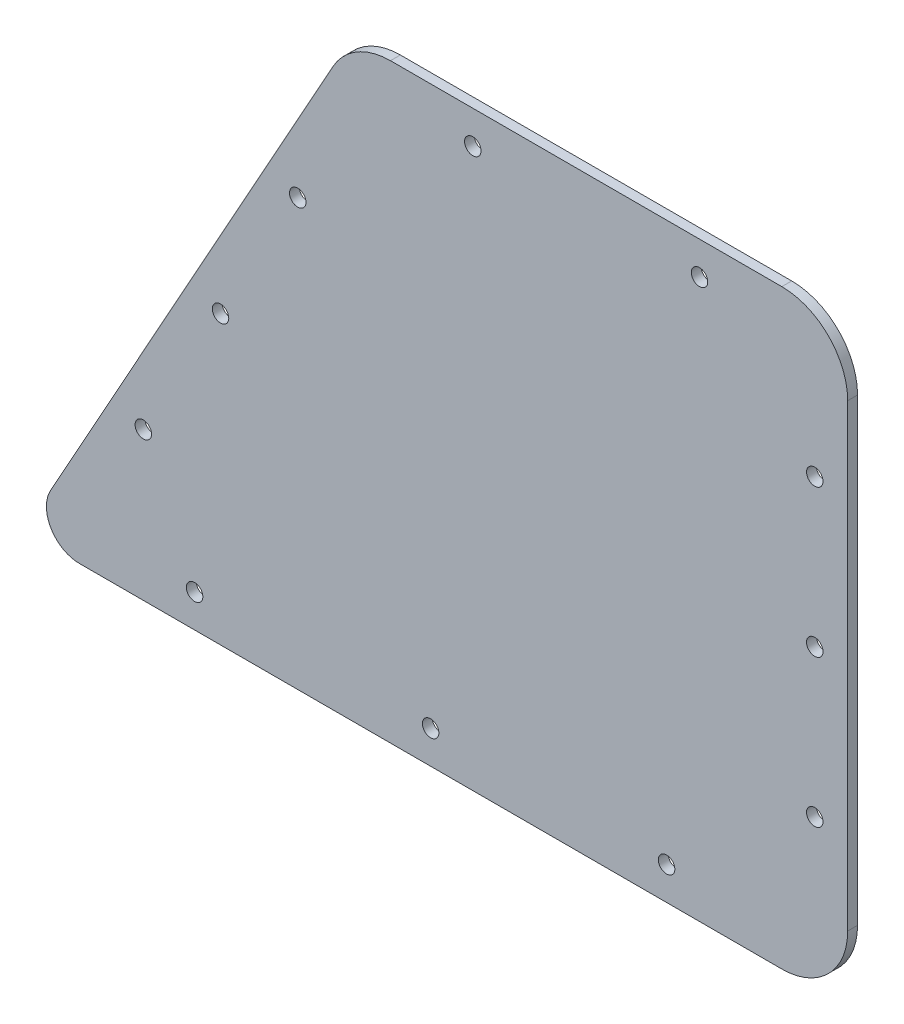
SolidWorks part; units mm, degrees
ref_plane "Front Plane" through (0, 0, 0) normal (0, 0, 1) x (1, 0, 0)
ref_plane "Top Plane" through (0, 0, 0) normal (0, 1, 0) x (1, 0, 0)
ref_plane "Right Plane" through (0, 0, 0) normal (1, 0, 0) x (0, 0, -1)
sketch "Sketch1" plane through (0, 0, 0) normal (0, 0, 1) x (1, 0, 0)
  line L0 (-1232.9818, 0) -> (48767.0182, 0) construction
  line L1 (-59.4361, 179.5) -> (59.4361, 179.5)
  line L2 (-76.9192, 169.2129) -> (-162.6728, 14.8564)
  line L3 (-153.9312, 0) -> (59.4361, 0)
  line L4 (79.4361, 20) -> (79.4361, 159.5)
  arc A0 (-153.9312, 0) -> (-162.6728, 14.8564) centre (-153.9312, 10) cw
  arc A1 (59.4361, 0) -> (79.4361, 20) centre (59.4361, 20) ccw
  arc A2 (79.4361, 159.5) -> (59.4361, 179.5) centre (59.4361, 159.5) ccw
  arc A3 (-76.9192, 169.2129) -> (-59.4361, 179.5) centre (-59.4361, 159.5) cw
  point P3 (0, 179.5)
  dimension "D1" = 10
  dimension "D2" = 20
  dimension "D3" = 20
  dimension "D4" = 20
  dimension "D5" = 179.5
  dimension "D6" = 176.5774
  dimension "D7" = 213.3673
extrude "Boss-Extrude1" add sketch "Sketch1" along normal blind 3
sketch "Sketch2" plane through (0, 0, 3) normal (0, 0, 1) x (1, 0, 0)
  line L0 (-34.4361, 184.5) -> (-34.4361, 169.5) construction
  line L1 (59.4361, 179.5) -> (-59.4361, 179.5) construction
  line L2 (79.4361, 20) -> (79.4361, 159.5) construction
  line L3 (-34.4361, 169.5) -> (34.4339, 169.5) construction
  line L4 (84.4361, 134.5) -> (69.4361, 134.5) construction
  line L5 (69.4361, 134.5) -> (69.4361, 89.75) construction
  line L6 (24.4361, -5) -> (24.4361, 10) construction
  line L7 (-153.9312, 0) -> (59.4361, 0) construction
  line L8 (24.4361, 10) -> (-47.2439, 10) construction
  line L9 (-147.6179, 52.2509) -> (-134.5055, 44.9663) construction
  line L11 (-76.9192, 169.2129) -> (-162.6728, 14.8564) construction
  line L12 (-134.5055, 44.9663) -> (-87.6021, 129.3924) construction
  circle A0 centre (-34.4361, 169.5) radius 2.5
  circle A1 centre (34.4339, 169.5) radius 2.5
  circle A2 centre (69.4361, 134.5) radius 2.5
  circle A3 centre (69.4361, 89.75) radius 2.5
  circle A4 centre (69.4361, 45) radius 2.5
  circle A5 centre (24.4361, 10) radius 2.5
  circle A6 centre (-47.2439, 10) radius 2.5
  circle A7 centre (-118.9239, 10) radius 2.5
  circle A8 centre (-134.5055, 44.9663) radius 2.5
  circle A9 centre (-87.6021, 129.3924) radius 2.5
  circle A10 centre (-111.0538, 87.1793) radius 2.5
  point P38 (0, 0)
  dimension "D1" = 5
  dimension "D2" = 15
  dimension "D3" = 5
  dimension "D4" = 113.8722
  dimension "D5" = 68.87
  dimension "D6" = 5
  dimension "D7" = 15
  dimension "D8" = 45
  dimension "D10" = 44.75
  dimension "D11" = 5
  dimension "D12" = 15
  dimension "D13" = 55
  dimension "D15" = 71.68
  dimension "D16" = 5
  dimension "D17" = 15
  dimension "D18" = 44.9663
  dimension "D19" = 96.58
  dimension "D9" = 3
  dimension "D14" = 3
extrude "Cut-Extrude1" cut sketch "Sketch2" against normal up to next
